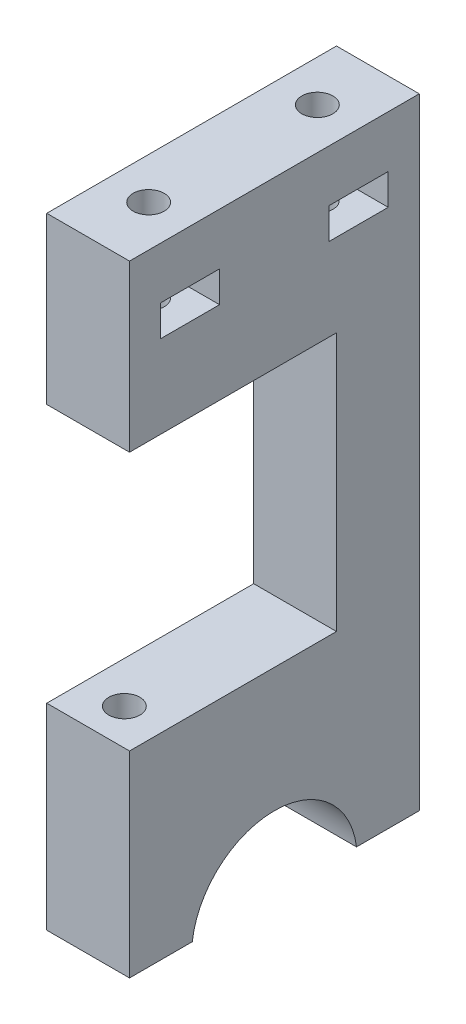
SolidWorks part; units mm, degrees
ref_plane "Front Plane" through (0, 0, 0) normal (0, 0, 1) x (1, 0, 0)
ref_plane "Top Plane" through (0, 0, 0) normal (0, 1, 0) x (1, 0, 0)
ref_plane "Right Plane" through (0, 0, 0) normal (1, 0, 0) x (0, 0, -1)
sketch "Sketch1" plane through (0, 0, 0) normal (0, 1, 0) x (1, 0, 0)
  line L1 (2, 21.8496) -> (10, 21.8496)
  line L2 (2, 21.8496) -> (2, -6.1504)
  line L3 (2, -6.1504) -> (10, -6.1504)
  line L4 (10, 21.8496) -> (10, -6.1504)
  dimension "D1" = 8
  dimension "D2" = 28
extrude "Boss-Extrude2" add sketch "Sketch1" along normal blind 60
sketch "Sketch5" plane through (10, 0, 0) normal (1, 0, 0) x (0, 0, -1)
  line L0 (21.8496, 0) -> (-6.1504, 0) construction
  line L1 (-6.1504, 60) -> (-6.1504, 0) construction
  line L2 (-0.0877, 0) -> (15.7868, 0)
  arc A0 (15.7868, 0) -> (-0.0877, 0) centre (7.8496, -1) ccw
  dimension "D1" = 16
  dimension "D3" = 14
  dimension "D2" = 1
extrude "Cut-Extrude2" cut sketch "Sketch5" against normal through all
sketch "Sketch6" plane through (0, 0, 0) normal (0, -1, 0) x (1, 0, 0)
  line L0 (2, -21.8496) -> (2, 6.1504) construction
  line L1 (2, -21.8496) -> (10, -21.8496) construction
  line L2 (2, 6.1504) -> (10, 6.1504) construction
  circle A0 centre (6, -18.3496) radius 1.5
  circle A1 centre (6, 2.6504) radius 1.5
  dimension "D1" = 3
  dimension "D2" = 4
  dimension "D3" = 3.5
  dimension "D4" = 3
  dimension "D5" = 4
  dimension "D6" = 3.5
extrude "Cut-Extrude3" cut sketch "Sketch6" against normal blind 25
sketch "Sketch7" plane through (2, 0, 0) normal (-1, 0, 0) x (0, 0, 1)
  line L0 (-21.8496, 60) -> (6.1504, 60) construction
  line L1 (-18.8496, 52) -> (-13.1496, 52)
  line L2 (-18.8496, 52) -> (-18.8496, 55)
  line L3 (-18.8496, 55) -> (-13.1496, 55)
  line L4 (-13.1496, 52) -> (-13.1496, 55)
  line L5 (-2.5496, 52) -> (3.1504, 52)
  line L6 (-2.5496, 52) -> (-2.5496, 55)
  line L7 (-2.5496, 55) -> (3.1504, 55)
  line L8 (3.1504, 52) -> (3.1504, 55)
  line L9 (-21.8496, 60) -> (-21.8496, 0) construction
  line L10 (6.1504, 60) -> (6.1504, 0) construction
  dimension "D1" = 5.7
  dimension "D2" = 5.7
  dimension "D3" = 5
  dimension "D4" = 5
  dimension "D5" = 3
  dimension "D6" = 3
  dimension "D7" = 3
  dimension "D8" = 3
extrude "Cut-Extrude4" cut sketch "Sketch7" against normal through all
sketch "Sketch8" plane through (0, 60, 0) normal (0, 1, 0) x (1, 0, 0)
  line L0 (10, 21.8496) -> (2, 21.8496) construction
  line L1 (10, -6.1504) -> (10, 21.8496) construction
  line L2 (2, -6.1504) -> (10, -6.1504) construction
  circle A0 centre (6, 15.9996) radius 1.5
  circle A2 centre (6, -0.3004) radius 1.5
  dimension "D1" = 5.85
  dimension "D2" = 4
  dimension "D3" = 3
  dimension "D4" = 5.85
  dimension "D5" = 4
  dimension "D6" = 3
extrude "Cut-Extrude5" cut sketch "Sketch8" against normal blind 25
sketch "Sketch9" plane through (10, 0, 0) normal (1, 0, 0) x (0, 0, -1)
  line L0 (-6.1504, 60) -> (-6.1504, 0) construction
  line L1 (-6.1504, 44) -> (13.8496, 44)
  line L2 (-6.1504, 44) -> (-6.1504, 19)
  line L3 (-6.1504, 19) -> (13.8496, 19)
  line L4 (13.8496, 44) -> (13.8496, 19)
  line L5 (-6.1504, 0) -> (-0.0877, 0) construction
  dimension "D1" = 25
  dimension "D2" = 19
  dimension "D3" = 20
extrude "Cut-Extrude6" cut sketch "Sketch9" against normal through all
